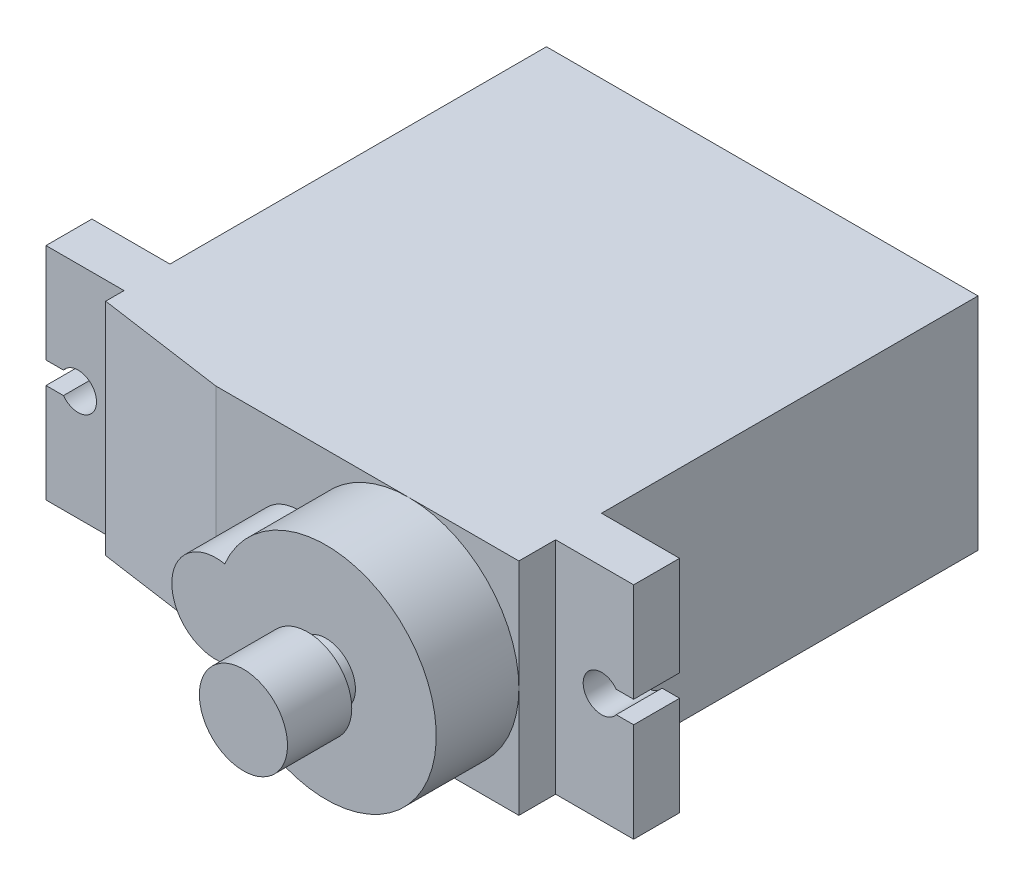
SolidWorks part; units mm, degrees
ref_plane "Front Plane" through (0, 0, 0) normal (0, 0, 1) x (1, 0, 0)
ref_plane "Top Plane" through (0, 0, 0) normal (0, 1, 0) x (1, 0, 0)
ref_plane "Right Plane" through (0, 0, 0) normal (1, 0, 0) x (0, 0, -1)
sketch "Sketch1" plane through (0, 0, 0) normal (0, 0, 1) x (1, 0, 0)
  line L0 (0, 11.1478) -> (0, -11.4656) construction
  line L1 (-13.0776, 0) -> (10.0353, 0) construction
  circle A0 centre (0, 0) radius 6
  dimension "D1" = 12
extrude "Boss-Extrude1" add sketch "Sketch1" along normal blind 6.5
sketch "Sketch2" plane through (0, 0, 0) normal (0, 0, 1) x (1, 0, 0)
  line L0 (0, 9.9674) -> (0, -12.5317) construction
  line L1 (-16.9469, 0) -> (10.4998, 0) construction
  line L2 (6, -6) -> (6, 6)
  line L3 (6, 6) -> (-17.5, 6)
  line L4 (-17.5, 6) -> (-17.5, -6)
  line L5 (6, -6) -> (-17.5, -6)
  circle A0 centre (0, 0) radius 6 construction
  point P12 (6, 0)
  point P13 (-17.5, 0)
  dimension "D1" = 23.5
  dimension "D2" = 6
extrude "Boss-Extrude2" add sketch "Sketch2" along normal blind 2
sketch "Sketch3" plane through (0, 0, 0) normal (0, 0, 1) x (1, 0, 0)
  line L0 (-5.75, 6) -> (-5.75, -6) construction
  line L3 (10.25, 6) -> (-21.75, 6)
  line L4 (-21.75, 6) -> (-21.75, 0.6)
  line L5 (-21.75, -6) -> (10.25, -6)
  line L6 (-20, 0) -> (-5.75, 0) construction
  line L7 (-21.75, 0.6) -> (-20.8, 0.6)
  line L8 (-21.75, -0.6) -> (-20.8, -0.6)
  line L9 (-21.75, -0.6) -> (-21.75, -6)
  line L10 (10.25, -0.6) -> (10.25, -6)
  line L11 (10.25, -0.6) -> (9.3, -0.6)
  line L12 (10.25, 0.6) -> (9.3, 0.6)
  line L13 (10.25, 6) -> (10.25, 0.6)
  line L14 (6, -6) -> (6, 0) construction
  line L16 (6, 6) -> (-17.5, 6) construction
  line L17 (-17.5, -6) -> (6, -6) construction
  arc A0 (-20.8, -0.6) -> (-20.8, 0.6) centre (-20, 0) ccw
  arc A1 (9.3, -0.6) -> (9.3, 0.6) centre (8.5, 0) cw
  dimension "D2" = 1
  dimension "D1" = 32
  dimension "D3" = 2.5
  dimension "D4" = 1.2
extrude "Boss-Extrude3" add sketch "Sketch3" against normal blind 2.5
sketch "Sketch4" plane through (0, 0, -2.5) normal (0, 0, -1) x (-1, 0, 0)
  line L4 (-6, 6) -> (-6, -6)
  line L5 (17.5, 6) -> (-6, 6)
  line L6 (17.5, -6) -> (17.5, 6)
  line L7 (-6, -6) -> (17.5, -6)
  line L8 (-6, 6) -> (-6, -6)
  line L9 (17.5, 6) -> (-6, 6)
  line L10 (17.5, -6) -> (17.5, 6)
  line L11 (-6, -6) -> (17.5, -6)
  dimension "D1" = 0
extrude "Boss-Extrude4" add sketch "Sketch4" along normal blind 20.5
sketch "Sketch5" plane through (0, 0, 2) normal (0, 0, 1) x (1, 0, 0)
  arc A0 (-5.52, 2.3515) -> (-5.52, -2.3515) centre (-6, 0) ccw
  circle A1 centre (0, 0) radius 6 construction
  circle A2 centre (0, 0) radius 6
  arc M1 (0, -6) -> (0, 6) centre (0, 0) cw
  dimension "D1" = 2.4
extrude "Boss-Extrude5" add sketch "Sketch5" along normal blind 4.5 contours A0 M1
sketch "Sketch6" plane through (0, 0, 6.5) normal (0, 0, 1) x (1, 0, 0)
  circle A0 centre (0, 0) radius 1.6
  dimension "D1" = 3.2
extrude "Boss-Extrude6" add sketch "Sketch6" along normal blind 1
sketch "Sketch7" plane through (0, 0, 7.5) normal (0, 0, 1) x (1, 0, 0)
  circle A0 centre (0, 0) radius 2.4
  dimension "D1" = 4.8
extrude "Boss-Extrude7" add sketch "Sketch7" along normal blind 3.5
chamfer "Chamfer1" distance 1 distance2 7 1 edges at (-17.5, 0, 2)
equation "\"、\"=18.5"
